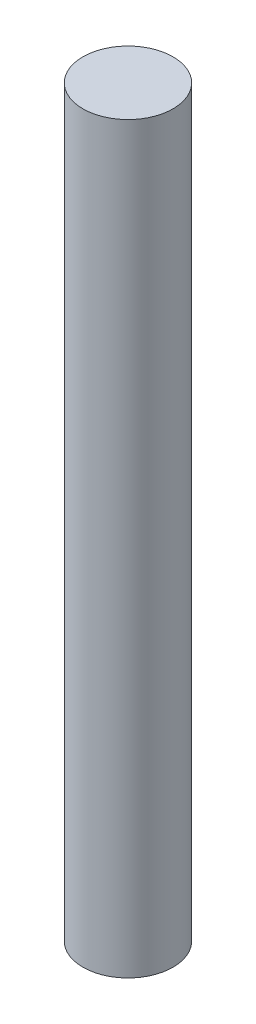
SolidWorks part; units mm, degrees
ref_plane "Front Plane" through (0, 0, 0) normal (0, 0, 1) x (1, 0, 0)
ref_plane "Top Plane" through (0, 0, 0) normal (0, 1, 0) x (1, 0, 0)
ref_plane "Right Plane" through (0, 0, 0) normal (1, 0, 0) x (0, 0, -1)
sketch "Sketch1" plane through (0, 0, 0) normal (0, 1, 0) x (1, 0, 0)
  circle A0 centre (0, 0) radius 4.85
  dimension "D1" = 9.7
extrude "Boss-Extrude1" add sketch "Sketch1" along normal blind 80
